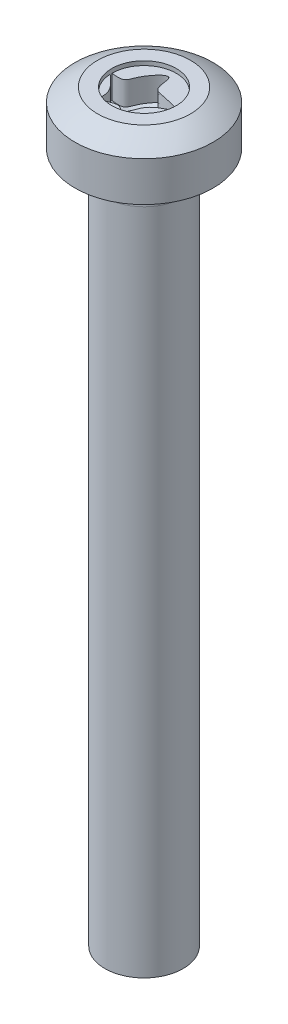
SolidWorks part; units mm, degrees
ref_plane "Front" through (0, 0, 0) normal (0, 0, 1) x (1, 0, 0)
ref_plane "Top" through (0, 0, 0) normal (0, 1, 0) x (1, 0, 0)
ref_plane "Right" through (0, 0, 0) normal (1, 0, 0) x (0, 0, -1)
sketch "Sketch1" plane through (0, 0, 0) normal (0, 0, 1) x (1, 0, 0)
  line L0 (0, 0) -> (0, 34.6184) construction
  line L1 (0, 0) -> (3.4, 0)
  line L2 (3.4, 0) -> (3.4, 60)
  line L3 (3.4, 60) -> (6, 60)
  line L4 (6, 60) -> (6, 64.6)
  line L5 (6, 64.6) -> (0, 64.6)
  line L6 (0, 64.6) -> (0, 0)
  line L7 (6, 60) -> (7, 60) construction
  line L8 (7, 60) -> (7, 22) construction
  dimension "HEAD_DIA" = 12
  dimension "HEAD_HT" = 4.6
  dimension "LENGTH" = 60
  dimension "DIA" = 6.8
  dimension "pitch" = 1
  dimension "thread_length" = 38
revolve "BODY" add sketch "Sketch1" angle 360 about L0
cosmetic thread "ThreadCosmetic" [suppressed] parameters "D1"=38, "D2"=5.7175
sketch "Sketch2" plane through (0, 0, 0) normal (0, 0, 1) x (1, 0, 0)
  line L0 (6, 63.45) -> (0, 55.45) construction
  line L3 (6, 60) -> (6, 64.6) construction
  line L4 (0, 0) -> (0, 34.6184) construction
  line L5 (0, 65.45) -> (0, 65.9322)
  line L6 (10, 55.45) -> (10, 65.9322)
  line L7 (10, 65.9322) -> (0, 65.9322)
  line L8 (0, 65.9322) -> (10, 65.9322)
  arc A0 (10, 55.45) -> (0, 65.45) centre (0, 55.45) ccw
  dimension "D1" = 1.15
  dimension "SPHERE_DIA" = 10
  dimension "D2" = 0.4822
revolve "HEAD-CUT" cut sketch "Sketch2" angle 360 about axis through (0, 0, 0) along (0, 1, 0)
sketch "Sketch4" plane through (0, 0, 0) normal (0, 0, 1) x (1, 0, 0)
  line L0 (-3.4, 58) -> (-3.2515, 59.75)
  line L1 (-3.4, 60) -> (-3.4, 0) construction
  line L2 (-3.4, 60) -> (-3.4, 58)
  arc A0 (-3.2515, 59.75) -> (-3.4, 60) centre (-3.5006, 59.7711) ccw
  dimension "D1" = 0.25
  dimension "CONER_RAD" = 0.25
  dimension "GAP" = 2
revolve "GAP" cut sketch "Sketch4" angle 360 about axis through (0, 0, 0) along (0, 1, 0)
sketch "Sketch5" plane through (0, 64.6, 0) normal (0, 1, 0) x (-1, 0, 0)
  line L0 (0, 2.1538) -> (0, 0) construction
  line L1 (0, 0) -> (1.4, 2.4249) construction
  circle A0 centre (0, 0) radius 2.1538 construction
  circle A1 centre (0, 0) radius 2.8
  spline S0 degree 3 poles (0.2303, 1.7651) (1.6246, 2.9563) (1.2917, 1.053) (3.7383, -0.275) (1.671, 0.1998) (1.4141, -1.1065) (-0.3154, -3.1176) (-0.0838, -0.7503) (-1.3658, -0.4438) (-3.8774, -0.0095) (-0.8848, 0.5534) (-0.7729, 2.8732) (0.2303, 1.7651) (1.6246, 2.9563) (1.2917, 1.053) knots -0.219874 -0.121327 -0.089152 0 0.052177 0.179018 0.237468 0.29204 0.415648 0.507115 0.541693 0.662365 0.780126 0.878673 0.910848 1 1.052177 1.179018 1.237468 only from (1.4, 2.4249) to (1.4, 2.4249)
  point P4 (0, 2.1538)
  point P5 (1.4, 2.4249)
  point P9 (2.3188, 0.8335)
  point P10 (1.56, 1.6058)
  point P11 (1.8653, -0.0192)
  point P12 (0.6107, -1.0962)
  point P13 (-0.9493, -0.5481)
  point P14 (-1.2546, 1.0769)
  point P15 (1.4, -0.7578)
  point P16 (-0.4375, -0.7578)
  point P19 (-1.3562, 0.8335)
  point P20 (-0.4375, 2.4249)
  dimension "slot_dia" = 5.6
  dimension "D3" = 4.3077
  dimension "D1" = 30
extrude "Recess-Cut-Extrude1" cut sketch "Sketch5" against normal blind 2.42
sketch "Sketch3" plane through (0, 0, 0) normal (0, 0, 1) x (1, 0, 0)
  line L0 (0, 60.9365) -> (2.1538, 62.18)
  line L1 (0, 0) -> (0, 34.6184) construction
  line L2 (2.1538, 62.18) -> (0, 62.18)
  line L3 (0, 62.18) -> (0, 60.9365)
  dimension "D1" = 60
  dimension "DRILL_RAD" = 2.1538
  dimension "SLOT_DEP" = 2.42
revolve "DRILL-CUT" cut sketch "Sketch3" angle 360 about axis through (0, 0, 0) along (0, 1, 0)
sketch "Sketch6" plane through (0, 0, 0) normal (0, 0, 1) x (1, 0, 0)
  line L0 (3.4, 0) -> (2.8587, 0.3125)
  line L1 (2.8587, 0.3125) -> (3.4, 0.625)
  line L4 (3.4, 0.625) -> (3.4, 0)
  line L5 (0, 0) -> (0, 34.6184) construction
  dimension "D1" = 2.8587
revolve "ThreadSchematic" [suppressed] cut sketch "Sketch6" angle 360 about axis through (0, 0, 0) along (0, 1, 0)
pattern_linear "ThdSchPat" [suppressed] count 38 spacing 1 along (0, 1, 0)
sketch "Sketch7" plane through (0, 64.6, 0) normal (0, 1, 0) x (-1, 0, 0)
  circle A0 centre (0, 0) radius 2.8
  dimension "D1" = 5.6
extrude "Recess-Cut-Extrude2" cut sketch "Sketch7" against normal blind 0.363
equation "\"D1@Sketch2\" = \"HEAD_HT@Sketch1\" * 0.25"
equation "\"D1@Sketch4\" = \"CONER_RAD@Sketch4\""
equation "\"D1@Recess-Cut-Extrude1\" = \"SLOT_DEP@Sketch3\""
equation "\"D1@Sketch7\" = \"slot_dia@Sketch5\""
equation "\"D1@Recess-Cut-Extrude2\" = \"SLOT_DEP@Sketch3\" * 0.15"
equation "\"D3@Sketch5\" = \"slot_dia@Sketch5\" / 1.3"
equation "\"DRILL_RAD@Sketch3\" = \"D3@Sketch5\" * 0.5"
equation "\"D1@ThreadCosmetic\" = \"thread_length@Sketch1\""
equation "\"D2@ThreadCosmetic\" = \"DIA@Sketch1\" - 1.0825 * \"pitch@Sketch1\""
equation "\"D1@Sketch6\" = \"D2@ThreadCosmetic\" / 2"
equation "\"D3@ThdSchPat\" = \"pitch@Sketch1\""
equation "\"D1@ThdSchPat\" = \"thread_length@Sketch1\" / \"pitch@Sketch1\""
